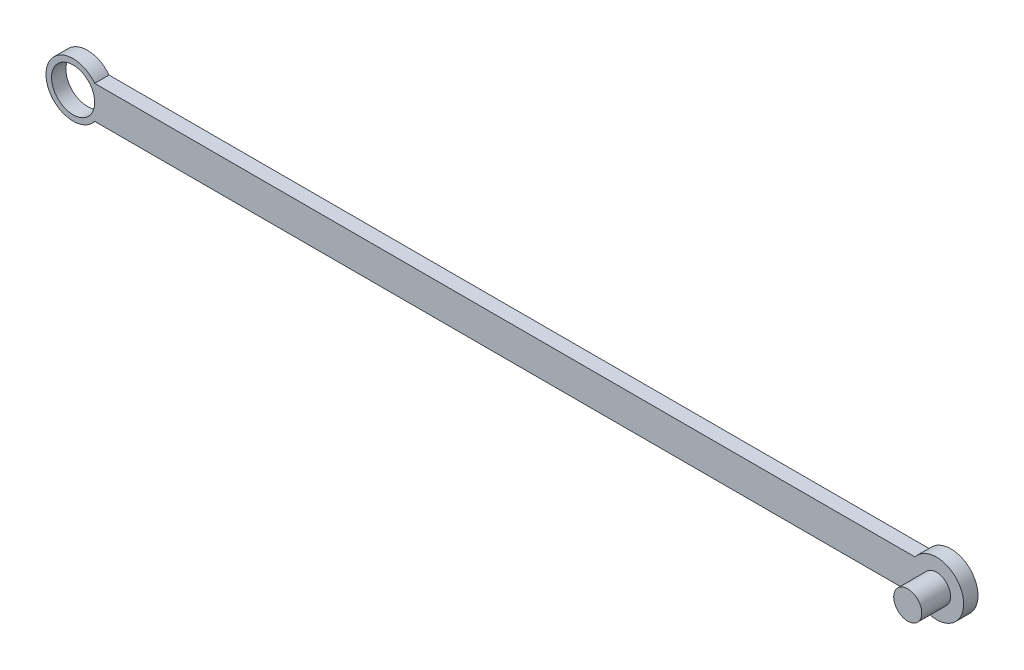
SolidWorks part; units mm, degrees
ref_plane "Front Plane" through (0, 0, 0) normal (0, 0, 1) x (1, 0, 0)
ref_plane "Top Plane" through (0, 0, 0) normal (0, 1, 0) x (1, 0, 0)
ref_plane "Right Plane" through (0, 0, 0) normal (1, 0, 0) x (0, 0, -1)
sketch "Sketch1" plane through (0, 0, 0) normal (0, 0, 1) x (1, 0, 0)
  line L1 (30, 1.8839) -> (30, 4.8645) construction
  line L3 (1.4972, 1.1435) -> (58.5028, 1.1435)
  line L4 (0, 0) -> (7.8135, 0) construction
  line L5 (1.4972, -1.1435) -> (58.5028, -1.1435)
  circle A0 centre (0, 0) radius 1.5
  arc A1 (0, 1.8839) -> (0, -1.8839) centre (0, 0) ccw
  arc A2 (60, 1.8839) -> (60, -1.8839) centre (60, 0) cw
  arc A3 (0, 1.8839) -> (1.4972, 1.1435) centre (0, 0) cw
  arc A4 (60, 1.8839) -> (58.5028, 1.1435) centre (60, 0) ccw
  arc A5 (58.5028, -1.1435) -> (60, -1.8839) centre (60, 0) ccw
  arc A6 (1.4972, -1.1435) -> (0, -1.8839) centre (0, 0) cw
  dimension "D1" = 3
extrude "Boss-Extrude1" add sketch "Sketch1" along normal blind 1
sketch "Sketch38" plane through (0, 0, 1) normal (0, 0, 1) x (1, 0, 0)
  circle A0 centre (60, 0) radius 0.975
  dimension "D1" = 1.95
extrude "Boss-Extrude2" add sketch "Sketch38" along normal blind 2
